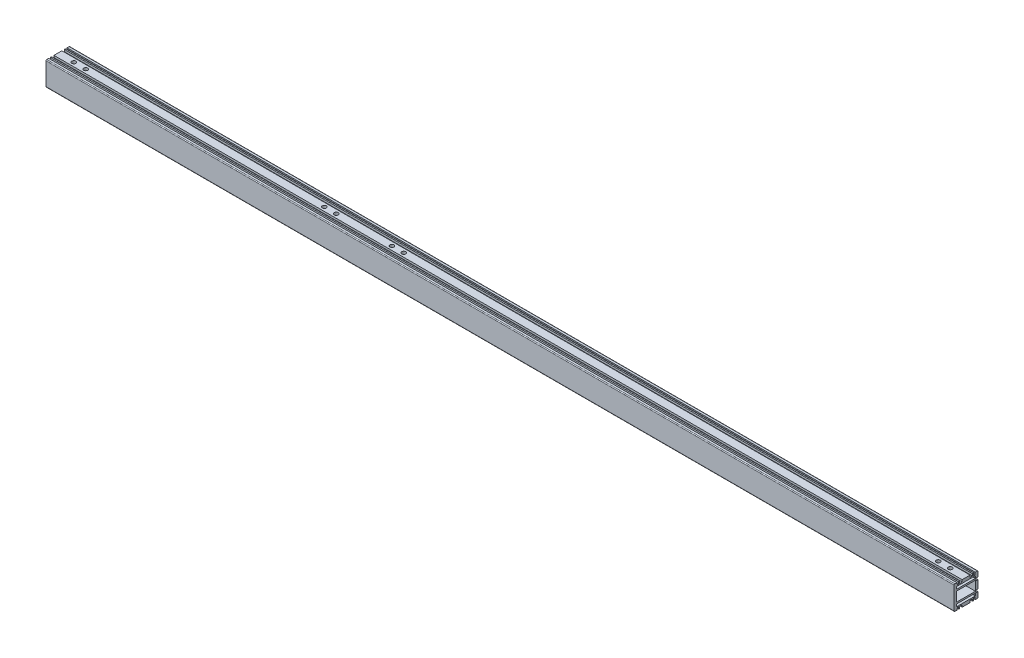
SolidWorks part; units mm, degrees
ref_plane "前视基准面" through (0, 0, 0) normal (0, 0, 1) x (1, 0, 0)
ref_plane "上视基准面" through (0, 0, 0) normal (0, 1, 0) x (1, 0, 0)
ref_plane "右视基准面" through (0, 0, 0) normal (1, 0, 0) x (0, 0, -1)
sketch "草图1" plane through (0, 0, 0) normal (1, 0, 0) x (0, 0, -1)
  line L0 (-15, 15) -> (15, -15) construction
  line L1 (-14, 15) -> (-11.5, 15)
  line L2 (-15, 14) -> (-15, -14)
  line L3 (-14, -15) -> (-11.5, -15)
  line L4 (15, 14) -> (15, 8)
  line L5 (15, 15) -> (-15, -15) construction
  line L6 (-11.5, 15) -> (-11.5, 13.5)
  line L7 (-11.5, 13.5) -> (-11.4, 13.5)
  line L8 (-11, 13.1) -> (-11, 12)
  line L9 (-11, 12) -> (-9.5, 12)
  line L10 (-9.5, 12) -> (-9.5, 15)
  line L11 (-9.5, 15) -> (-8, 15)
  line L12 (-8, 15) -> (-8, 12.5)
  line L13 (-8, 12.5) -> (-5, 12.5)
  line L14 (-5, 12.5) -> (-5, 15)
  line L15 (-5, 15) -> (5, 15)
  line L16 (0, 21.5201) -> (0, -18.309) construction
  line L17 (0, 55) -> (0, -55) construction
  line L18 (5, 12.5) -> (5, 15)
  line L19 (8, 12.5) -> (5, 12.5)
  line L20 (8, 15) -> (8, 12.5)
  line L21 (9.5, 15) -> (8, 15)
  line L22 (9.5, 12) -> (9.5, 15)
  line L23 (11, 12) -> (9.5, 12)
  line L24 (11, 13.1) -> (11, 12)
  line L25 (11.5, 13.5) -> (11.4, 13.5)
  line L26 (11.5, 15) -> (11.5, 13.5)
  line L27 (8, 15) -> (9.5, 15)
  line L28 (11.5, 15) -> (14, 15)
  line L29 (-19.8303, 0) -> (22.13, 0) construction
  line L30 (55, 0) -> (-55, 0) construction
  line L31 (8, -15) -> (9.5, -15)
  line L32 (11.5, -15) -> (11.5, -13.5)
  line L33 (11.5, -13.5) -> (11.4, -13.5)
  line L34 (11, -13.1) -> (11, -12)
  line L35 (11, -12) -> (9.5, -12)
  line L36 (9.5, -12) -> (9.5, -15)
  line L37 (9.5, -15) -> (8, -15)
  line L38 (8, -15) -> (8, -12.5)
  line L39 (8, -12.5) -> (5, -12.5)
  line L40 (5, -12.5) -> (5, -15)
  line L41 (-5, -15) -> (5, -15)
  line L42 (-5, -12.5) -> (-5, -15)
  line L43 (-8, -12.5) -> (-5, -12.5)
  line L44 (-8, -15) -> (-8, -12.5)
  line L45 (-9.5, -15) -> (-8, -15)
  line L46 (-9.5, -12) -> (-9.5, -15)
  line L47 (-11, -12) -> (-9.5, -12)
  line L48 (-11, -13.1) -> (-11, -12)
  line L49 (-11.5, -13.5) -> (-11.4, -13.5)
  line L50 (-11.5, -15) -> (-11.5, -13.5)
  line L51 (-9.5, -15) -> (-8, -15)
  line L52 (-5, -15) -> (5, -15)
  line L53 (8, -15) -> (9.5, -15)
  line L54 (11.5, -15) -> (14, -15)
  line L55 (15, 8) -> (12.5, 8)
  line L56 (12.5, 8) -> (12.5, 5)
  line L57 (12.5, 5) -> (15, 5)
  line L58 (12.5, -5) -> (15, -5)
  line L59 (12.5, -8) -> (12.5, -5)
  line L60 (15, -8) -> (12.5, -8)
  line L61 (15, 5) -> (15, -5)
  line L62 (15, -8) -> (15, -14)
  line L63 (12, -10.5) -> (12, -8.5)
  line L64 (-11.5, 11) -> (11.5, 11)
  line L65 (-12, 10.5) -> (-12, 8.5)
  line L66 (-11.5, 8) -> (11.5, 8)
  line L67 (12, 10.5) -> (12, 8.5)
  line L68 (-11.5, -8) -> (11.5, -8)
  line L69 (-12, -10.5) -> (-12, -8.5)
  line L70 (-11.5, -11) -> (11.5, -11)
  line L72 (-11.75, 6) -> (11.75, 6)
  line L73 (-11.75, 6) -> (-11.75, -6)
  line L74 (-11.75, -6) -> (11.75, -6)
  line L75 (11.75, 6) -> (11.75, -6)
  arc A0 (12, 8.5) -> (11.5, 8) centre (11.5, 8.5) cw
  arc A1 (11.5, 11) -> (12, 10.5) centre (11.5, 10.5) cw
  arc A2 (-11.5, 11) -> (-12, 10.5) centre (-11.5, 10.5) ccw
  arc A3 (-11.5, 8) -> (-12, 8.5) centre (-11.5, 8.5) cw
  arc A4 (-11, -13.1) -> (-11.4, -13.5) centre (-11.4, -13.1) cw
  arc A5 (11.4, -13.5) -> (11, -13.1) centre (11.4, -13.1) cw
  arc A6 (11.4, 13.5) -> (11, 13.1) centre (11.4, 13.1) ccw
  arc A7 (-11, 13.1) -> (-11.4, 13.5) centre (-11.4, 13.1) ccw
  arc A8 (-11.5, -8) -> (-12, -8.5) centre (-11.5, -8.5) ccw
  arc A9 (-11.5, -11) -> (-12, -10.5) centre (-11.5, -10.5) cw
  arc A10 (11.5, -11) -> (12, -10.5) centre (11.5, -10.5) ccw
  arc A11 (12, -8.5) -> (11.5, -8) centre (11.5, -8.5) ccw
  arc A12 (14, 15) -> (15, 14) centre (14, 14) cw
  arc A13 (14, -15) -> (15, -14) centre (14, -14) ccw
  arc A14 (-15, -14) -> (-14, -15) centre (-14, -14) ccw
  arc A15 (-15, 14) -> (-14, 15) centre (-14, 14) cw
  point P69 (12, 11)
  point P72 (-12, 11)
  point P77 (-11, -13.5)
  point P80 (11, -13.5)
  point P83 (11, 13.5)
  point P86 (-11, 13.5)
  point P99 (-12, -11)
  point P100 (12, -11)
  dimension "D17" = 0.5
  dimension "D18" = 0.4
  dimension "D21" = 1
  dimension "D1" = 3.5
  dimension "D2" = 1.5
  dimension "D3" = 0.5
  dimension "D4" = 1.5
  dimension "D5" = 3
  dimension "D6" = 30
  dimension "D7" = 30
  dimension "D8" = 1.5
  dimension "D9" = 2.5
  dimension "D10" = 3
  dimension "D11" = 2.5
  dimension "D12" = 7
  dimension "D13" = 3
  dimension "D14" = 4
  dimension "D15" = 3
  dimension "D16" = 24
  dimension "D19" = 23.5
  dimension "D20" = 12
extrude "凸台-拉伸1" add sketch "草图1" along normal mid plane 1142 contours A15 L2 A14 L3 L50 L49 A4 L48 L47 L46 L45 L44 L43 L42 L41 L40 L39 L38 L31 L36 L35 L34 A5 L33 L32 L54 A13 L62 L60 L59 L58 L61 L57 L56 L55 L4 A12 L28 L26 L25 A6 L24 L23 L22 L21 L20 L19 L18 L15 L14 L13
hole_wizard "M6 螺纹孔1" positions "草图3" profile "草图2" tap size "M6" standard "GB"
sketch "草图3" plane through (0, 15, 0) normal (0, 1, 0) x (-1, 0, 0)
  line L0 (571, 5) -> (571, -5) construction
  line L1 (-571, 15) -> (571, 15) construction
  point P0 (551, 0)
  point P1 (536, 0)
  point P4 (236, 0)
  point P7 (221, 0)
  point P10 (151, 0)
  point P13 (136, 0)
  point P16 (-536, 0)
  point P19 (-551, 0)
  dimension "D1" = 20
  dimension "D2" = 15
sketch "草图2" plane through (-551, 15, 0) normal (1, 0, 0) x (0, 0, 1)
  line L0 (0, 0) -> (0, 16.5022)
  line L1 (0, 16.5022) -> (2.5, 15)
  line L2 (2.5, 15) -> (2.5, 0)
  line L5 (2.5, 0) -> (0, 0)
  line L10 (0, 16.5022) -> (-2.5, 15) construction
  line L11 (0, -6.35) -> (0, 107.95) construction
  dimension "螺纹孔钻头直径" = 5
  dimension "螺纹孔钻头深度" = 15
  dimension "导头角度" = 118
cosmetic thread "孔螺蚊线1" parameters "D1"=9, "D2"=6
cosmetic thread "孔螺蚊线2" parameters "D1"=9, "D2"=6
cosmetic thread "孔螺蚊线3" parameters "D1"=9, "D2"=6
cosmetic thread "孔螺蚊线4" parameters "D1"=9, "D2"=6
cosmetic thread "孔螺蚊线5" parameters "D1"=9, "D2"=6
cosmetic thread "孔螺蚊线6" parameters "D1"=9, "D2"=6
cosmetic thread "孔螺蚊线7" parameters "D1"=9, "D2"=6
cosmetic thread "孔螺蚊线8" parameters "D1"=9, "D2"=6
hole_wizard "M6 螺纹孔2" positions "草图5" profile "草图4" tap size "M6" standard "GB"
sketch "草图5" plane through (0, -15, 0) normal (0, -1, 0) x (1, 0, 0)
  line L0 (-571, 5) -> (-571, -5) construction
  line L1 (571, 15) -> (-571, 15) construction
  point P0 (-551, 0)
  point P1 (-536, 0)
  point P4 (536, 0)
  point P7 (551, 0)
  dimension "D1" = 20
  dimension "D2" = 15
sketch "草图4" plane through (-551, -15, 0) normal (1, 0, 0) x (0, 0, -1)
  line L0 (0, 0) -> (0, 16.5022)
  line L1 (0, 16.5022) -> (2.5, 15)
  line L2 (2.5, 15) -> (2.5, 0)
  line L5 (2.5, 0) -> (0, 0)
  line L10 (0, 16.5022) -> (-2.5, 15) construction
  line L11 (0, -6.35) -> (0, 107.95) construction
  dimension "螺纹孔钻头直径" = 5
  dimension "螺纹孔钻头深度" = 15
  dimension "导头角度" = 118
cosmetic thread "孔螺蚊线9" parameters "D1"=9, "D2"=6
cosmetic thread "孔螺蚊线10" parameters "D1"=9, "D2"=6
cosmetic thread "孔螺蚊线11" parameters "D1"=9, "D2"=6
cosmetic thread "孔螺蚊线12" parameters "D1"=9, "D2"=6
hole_wizard "M6 螺纹孔3" positions "草图7" profile "草图6" tap size "M6" standard "GB"
sketch "草图7" plane through (0, 0, -15) normal (0, 0, -1) x (-1, 0, 0)
  line L0 (-571, -15) -> (571, -15) construction
  line L1 (571, 5) -> (571, -5) construction
  point P0 (293.5, 0)
  point P1 (218.5, 0)
  dimension "D1" = 15
  dimension "D2" = 15
  dimension "D3" = 75
  dimension "D4" = 277.5
sketch "草图6" plane through (-293.5, 0, -15) normal (1, 0, 0) x (0, 1, 0)
  line L0 (0, 0) -> (0, 16.5022)
  line L1 (0, 16.5022) -> (2.5, 15)
  line L2 (2.5, 15) -> (2.5, 0)
  line L5 (2.5, 0) -> (0, 0)
  line L10 (0, 16.5022) -> (-2.5, 15) construction
  line L11 (0, -6.35) -> (0, 107.95) construction
  dimension "螺纹孔钻头直径" = 5
  dimension "螺纹孔钻头深度" = 15
  dimension "导头角度" = 118
cosmetic thread "孔螺蚊线13" parameters "D1"=3.25, "D2"=6
cosmetic thread "孔螺蚊线14" parameters "D1"=3.25, "D2"=6
hole_wizard "M4 螺纹孔1" positions "草图9" profile "草图8" tap size "M4" standard "GB"
sketch "草图9" plane through (0, -15, 0) normal (0, -1, 0) x (1, 0, 0)
  line L2 (-571, 14) -> (-571, 11.5) construction
  line L3 (571, 15) -> (-571, 15) construction
  point P3 (-326, 0)
  point P5 (-131, 0)
  point P7 (64, 0)
  point P9 (259, 0)
  point P11 (454, 0)
  dimension "D1" = 15
  dimension "D2" = 245
  dimension "D4" = 195
  dimension "D5" = 195
  dimension "D6" = 195
  dimension "D7" = 195
sketch "草图8" plane through (-326, -15, 0) normal (1, 0, 0) x (0, 0, -1)
  line L0 (0, 0) -> (0, 11.0914)
  line L1 (0, 11.0914) -> (1.65, 10.1)
  line L2 (1.65, 10.1) -> (1.65, 0)
  line L5 (1.65, 0) -> (0, 0)
  line L10 (0, 11.0914) -> (-1.65, 10.1) construction
  line L11 (0, -6.35) -> (0, 107.95) construction
  dimension "螺纹孔钻头直径" = 3.3
  dimension "螺纹孔钻头深度" = 10.1
  dimension "导头角度" = 118
cosmetic thread "孔螺蚊线15" parameters "D1"=8, "D2"=4
cosmetic thread "孔螺蚊线16" parameters "D1"=8, "D2"=4
cosmetic thread "孔螺蚊线17" parameters "D1"=8, "D2"=4
cosmetic thread "孔螺蚊线18" parameters "D1"=8, "D2"=4
cosmetic thread "孔螺蚊线19" parameters "D1"=8, "D2"=4
